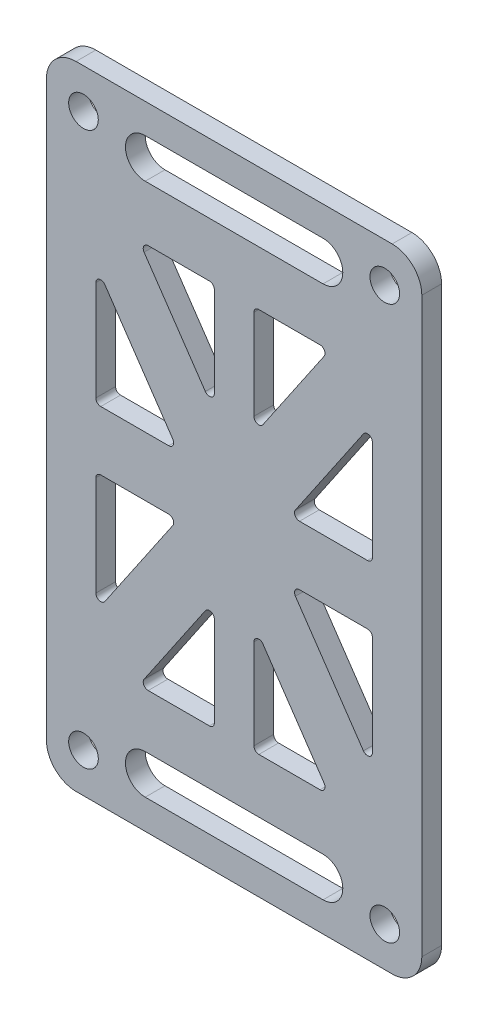
SolidWorks part; units mm, degrees
ref_plane "前视基准面" through (0, 0, 0) normal (0, 0, 1) x (1, 0, 0)
ref_plane "上视基准面" through (0, 0, 0) normal (0, 1, 0) x (1, 0, 0)
ref_plane "右视基准面" through (0, 0, 0) normal (1, 0, 0) x (0, 0, -1)
sketch "草图1" plane through (0, 0, 0) normal (0, 0, 1) x (1, 0, 0)
  line L0 (-19, 0) -> (19, 0) construction
  line L1 (-16, 32) -> (16, 32)
  line L2 (-19, 29) -> (-19, -29)
  line L3 (-16, -32) -> (16, -32)
  line L4 (19, 29) -> (19, -29)
  line L5 (-19, 32) -> (19, -32) construction
  line L6 (-19, -32) -> (19, 32) construction
  line L7 (-16, 23.5) -> (16, 23.5) construction
  line L8 (-16, 23.5) -> (-16, -23.5) construction
  line L9 (-16, -23.5) -> (16, -23.5) construction
  line L10 (16, 23.5) -> (16, -23.5) construction
  line L11 (-16, 23.5) -> (16, -23.5) construction
  line L12 (-16, -23.5) -> (16, 23.5) construction
  line L13 (19, 0) -> (0, 0) construction
  line L14 (0, 32) -> (0, -32) construction
  line L15 (-9, -27) -> (9, -27) construction
  line L18 (-9, -25) -> (9, -25)
  line L19 (-9, -29) -> (9, -29)
  line L20 (-9, 27) -> (9, 27) construction
  line L21 (-9, 25) -> (9, 25)
  line L22 (-9, 29) -> (9, 29)
  line L23 (-6.6172, 3) -> (-13.5, 3)
  line L24 (-14, 3.5) -> (-14, 13.6091)
  line L25 (-13.0867, 13.8905) -> (-6.2039, 3.7814)
  line L26 (14, 3.5) -> (14, 13.6091)
  line L27 (6.6172, 3) -> (13.5, 3)
  line L28 (13.0867, 13.8905) -> (6.2039, 3.7814)
  line L29 (6.6172, -3) -> (13.5, -3)
  line L30 (13.0867, -13.8905) -> (6.2039, -3.7814)
  line L31 (14, -3.5) -> (14, -13.6091)
  line L32 (-14, -3.5) -> (-14, -13.6091)
  line L33 (-6.6172, -3) -> (-13.5, -3)
  line L34 (-13.0867, -13.8905) -> (-6.2039, -3.7814)
  line L35 (-8.702, 19.5) -> (-2.5, 19.5)
  line L36 (-2, 19) -> (-2, 9.8909)
  line L37 (-2.9133, 9.6095) -> (-9.1153, 18.7186)
  line L38 (2, 19) -> (2, 9.8909)
  line L39 (8.702, 19.5) -> (2.5, 19.5)
  line L40 (2.9133, 9.6095) -> (9.1153, 18.7186)
  line L41 (8.702, -19.5) -> (2.5, -19.5)
  line L42 (2.9133, -9.6095) -> (9.1153, -18.7186)
  line L43 (2, -19) -> (2, -9.8909)
  line L44 (-2, -19) -> (-2, -9.8909)
  line L45 (-8.702, -19.5) -> (-2.5, -19.5)
  line L46 (-2.9133, -9.6095) -> (-9.1153, -18.7186)
  circle A1 centre (-15.25, 28) radius 1.5
  circle A2 centre (15.25, 28) radius 1.5
  circle A3 centre (15.25, -28) radius 1.5
  circle A4 centre (-15.25, -28) radius 1.5
  arc A5 (-16, 32) -> (-19, 29) centre (-16, 29) ccw
  arc A6 (-19, -29) -> (-16, -32) centre (-16, -29) ccw
  arc A7 (16, -32) -> (19, -29) centre (16, -29) ccw
  arc A8 (16, 32) -> (19, 29) centre (16, 29) cw
  arc A11 (-9, -25) -> (-9, -29) centre (-9, -27) ccw
  arc A12 (9, -29) -> (9, -25) centre (9, -27) ccw
  arc A13 (-9, 25) -> (-9, 29) centre (-9, 27) cw
  arc A14 (9, 29) -> (9, 25) centre (9, 27) cw
  arc A15 (-13.5, 3) -> (-14, 3.5) centre (-13.5, 3.5) cw
  arc A16 (-6.6172, 3) -> (-6.2039, 3.7814) centre (-6.6172, 3.5) ccw
  arc A17 (-14, 13.6091) -> (-13.0867, 13.8905) centre (-13.5, 13.6091) cw
  arc A18 (13.5, 3) -> (14, 3.5) centre (13.5, 3.5) ccw
  arc A19 (6.6172, 3) -> (6.2039, 3.7814) centre (6.6172, 3.5) cw
  arc A20 (14, 13.6091) -> (13.0867, 13.8905) centre (13.5, 13.6091) ccw
  arc A21 (13.5, -3) -> (14, -3.5) centre (13.5, -3.5) cw
  arc A22 (6.6172, -3) -> (6.2039, -3.7814) centre (6.6172, -3.5) ccw
  arc A23 (14, -13.6091) -> (13.0867, -13.8905) centre (13.5, -13.6091) cw
  arc A24 (-13.5, -3) -> (-14, -3.5) centre (-13.5, -3.5) ccw
  arc A25 (-6.6172, -3) -> (-6.2039, -3.7814) centre (-6.6172, -3.5) cw
  arc A26 (-14, -13.6091) -> (-13.0867, -13.8905) centre (-13.5, -13.6091) ccw
  arc A27 (-2.5, 19.5) -> (-2, 19) centre (-2.5, 19) cw
  arc A28 (-8.702, 19.5) -> (-9.1153, 18.7186) centre (-8.702, 19) ccw
  arc A29 (-2, 9.8909) -> (-2.9133, 9.6095) centre (-2.5, 9.8909) cw
  arc A30 (2.5, 19.5) -> (2, 19) centre (2.5, 19) ccw
  arc A31 (8.702, 19.5) -> (9.1153, 18.7186) centre (8.702, 19) cw
  arc A32 (2, 9.8909) -> (2.9133, 9.6095) centre (2.5, 9.8909) ccw
  arc A33 (2.5, -19.5) -> (2, -19) centre (2.5, -19) cw
  arc A34 (8.702, -19.5) -> (9.1153, -18.7186) centre (8.702, -19) ccw
  arc A35 (2, -9.8909) -> (2.9133, -9.6095) centre (2.5, -9.8909) cw
  arc A36 (-2.5, -19.5) -> (-2, -19) centre (-2.5, -19) ccw
  arc A37 (-8.702, -19.5) -> (-9.1153, -18.7186) centre (-8.702, -19) cw
  arc A38 (-2, -9.8909) -> (-2.9133, -9.6095) centre (-2.5, -9.8909) ccw
  point P0 (0, 0)
  point P6 (0, 0)
  point P17 (0, 0)
  point P20 (0, 0)
  point P29 (0, -27)
  point P48 (0, 27)
  dimension "D5" = 3
  dimension "D8" = 3
  dimension "D9" = 3
  dimension "D10" = 2
  dimension "D16" = 0.5
  dimension "D20" = 0.5
  dimension "D1" = 64
  dimension "D2" = 38
  dimension "D3" = 47
  dimension "D4" = 32
  dimension "D6" = 56
  dimension "D7" = 30.5
  dimension "D11" = 3
  dimension "D12" = 18
  dimension "D13" = 3
  dimension "D14" = 2
  dimension "D15" = 3
  dimension "D17" = 2
  dimension "D18" = 3
  dimension "D19" = 4
extrude "凸台-拉伸1" add sketch "草图1" along normal blind 2
